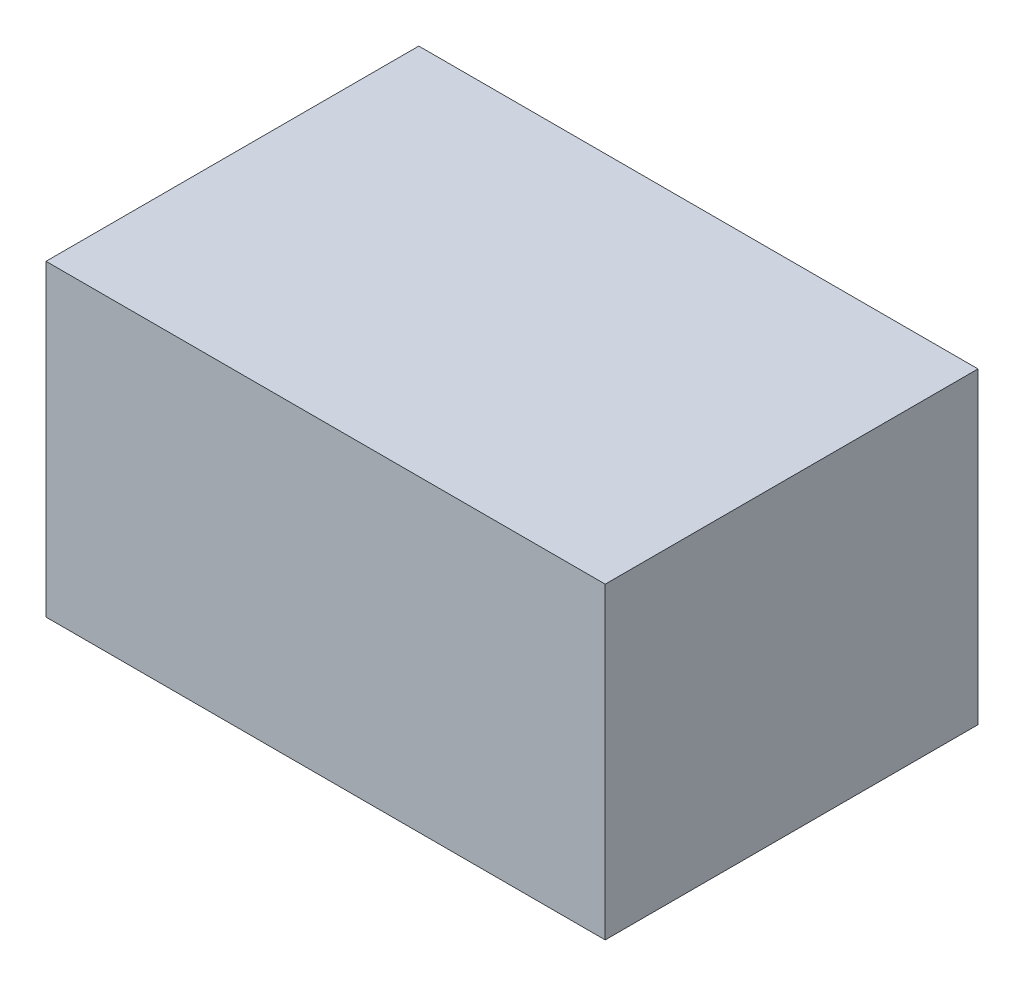
SolidWorks part; units mm, degrees
ref_plane "Front Plane" through (0, 0, 0) normal (0, 0, 1) x (1, 0, 0)
ref_plane "Top Plane" through (0, 0, 0) normal (0, 1, 0) x (1, 0, 0)
ref_plane "Right Plane" through (0, 0, 0) normal (1, 0, 0) x (0, 0, -1)
sketch "Sketch2" plane through (0, 0, 0) normal (0, 0, 1) x (1, 0, 0)
  line L1 (-150, -82.6534) -> (150, -82.6534)
  line L2 (-150, -82.6534) -> (-150, 82.6534)
  line L3 (-150, 82.6534) -> (150, 82.6534)
  line L4 (150, -82.6534) -> (150, 82.6534)
  line L5 (-150, -82.6534) -> (150, 82.6534) construction
  line L6 (-150, 82.6534) -> (150, -82.6534) construction
  point P0 (0, 0)
  dimension "D1" = 300
extrude "Boss-Extrude1" add sketch "Sketch2" along normal blind 200
